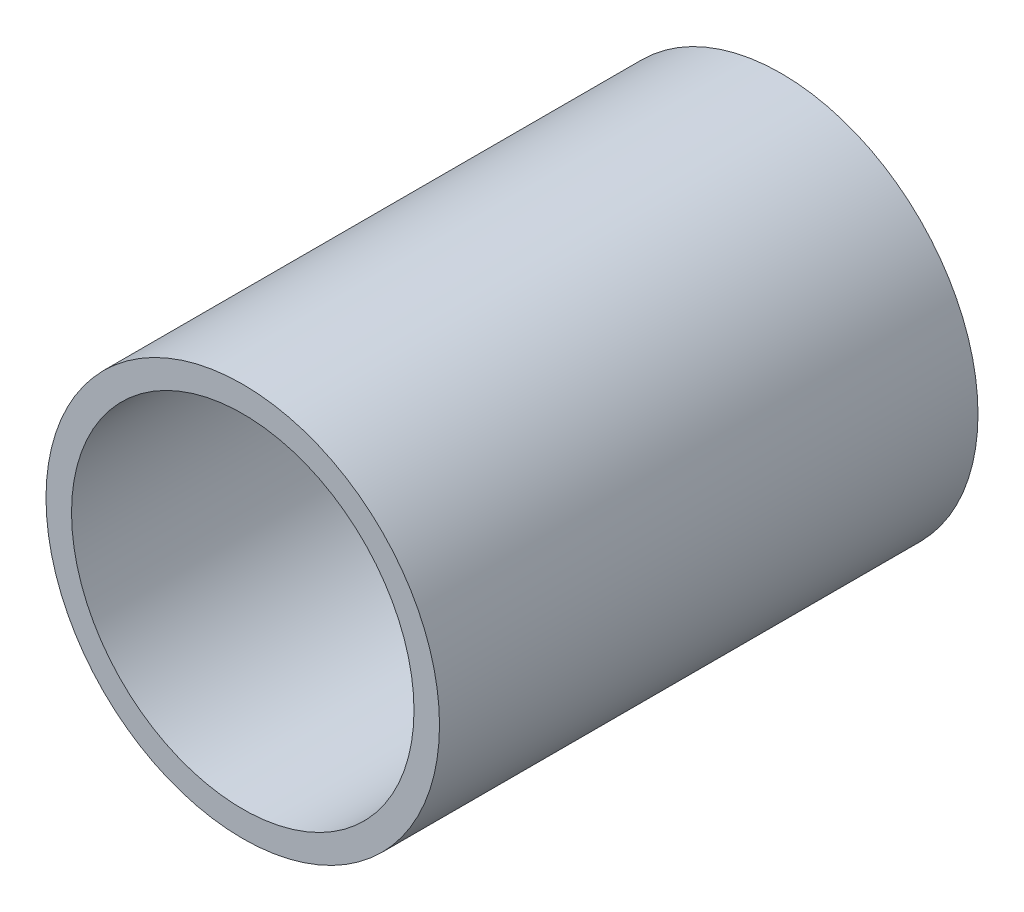
SolidWorks part; units mm, degrees
ref_plane "Front Plane" through (0, 0, 0) normal (0, 0, 1) x (1, 0, 0)
ref_plane "Top Plane" through (0, 0, 0) normal (0, 1, 0) x (1, 0, 0)
ref_plane "Right Plane" through (0, 0, 0) normal (1, 0, 0) x (0, 0, -1)
sketch "Sketch1" plane through (0, 0, 0) normal (0, 0, 1) x (1, 0, 0)
  circle A0 centre (0, 0) radius 30.1625
  circle A1 centre (0, 0) radius 26.2509
  dimension "D1" = 60.325
  dimension "D2" = 3.9116
extrude "Boss-Extrude1" add sketch "Sketch1" along normal blind 82.55
